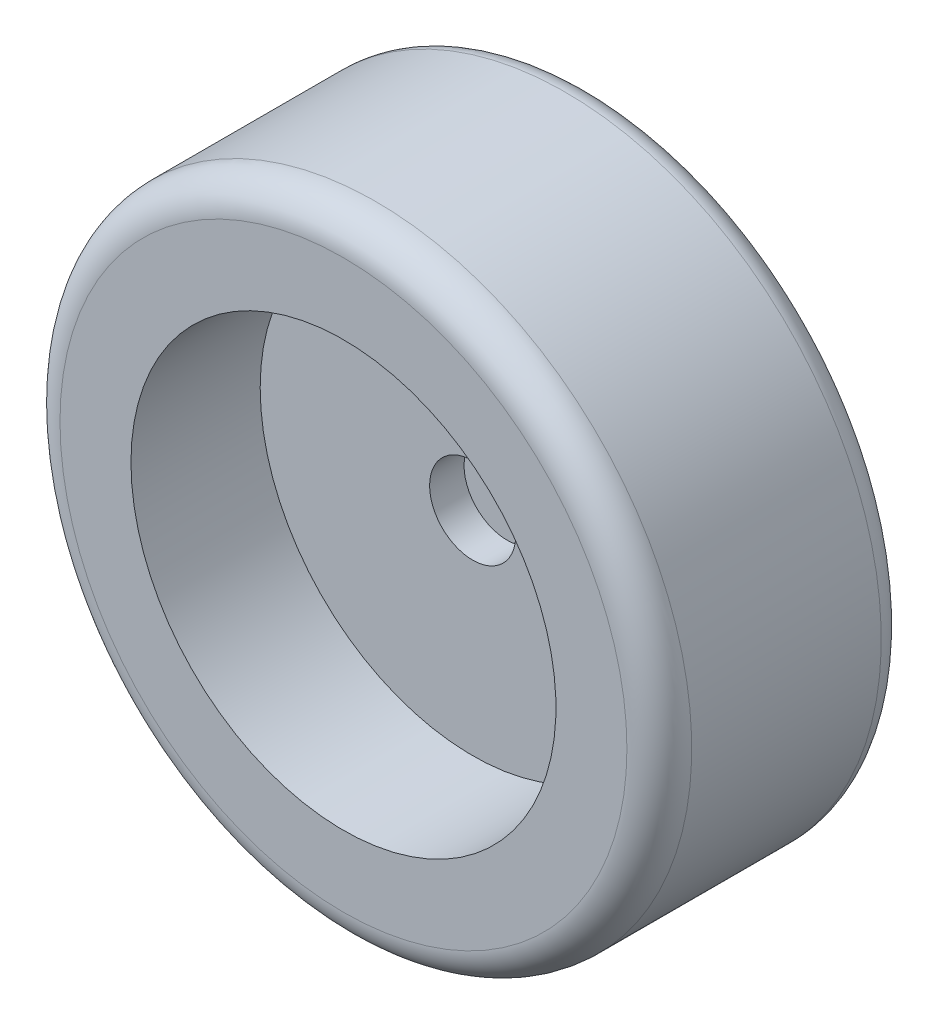
SolidWorks part; units mm, degrees
ref_plane "Front Plane" through (0, 0, 0) normal (0, 0, 1) x (1, 0, 0)
ref_plane "Top Plane" through (0, 0, 0) normal (0, 1, 0) x (1, 0, 0)
ref_plane "Right Plane" through (0, 0, 0) normal (1, 0, 0) x (0, 0, -1)
ref_plane "Plane1" through (0, 0, 0) normal (0, -1, 0) x (1, 0, 0)
sketch "Sketch1" plane through (0, 0, 0) normal (0, -1, 0) x (1, 0, 0)
  line L0 (7.5, 14.5) -> (0, 14.5)
  line L1 (0, 14.5) -> (0, 0)
  line L2 (0, 0) -> (50.6433, 0)
  line L3 (55, 4.3567) -> (55, 37.3567)
  line L4 (49.3567, 43) -> (37, 43)
  line L5 (37, 43) -> (37, 20.5)
  line L6 (37, 20.5) -> (7.5, 20.5)
  line L7 (7.5, 20.5) -> (7.5, 14.5)
  line L8 (0, 43) -> (0, 0) construction
  arc A0 (50.6433, 0) -> (55, 4.3567) centre (50.6433, 4.3567) ccw
  arc A1 (55, 37.3567) -> (49.3567, 43) centre (49.3567, 37.3567) ccw
  point P13 (0, 0)
  dimension "D7" = 4.3567
  dimension "D8" = 5.6433
  dimension "D1" = 14.5
  dimension "D2" = 43
  dimension "D3" = 55
  dimension "D4" = 6
  dimension "D5" = 29.5
  dimension "D6" = 7.5
revolve "Revolve1" add sketch "Sketch1" angle 360 about L8
